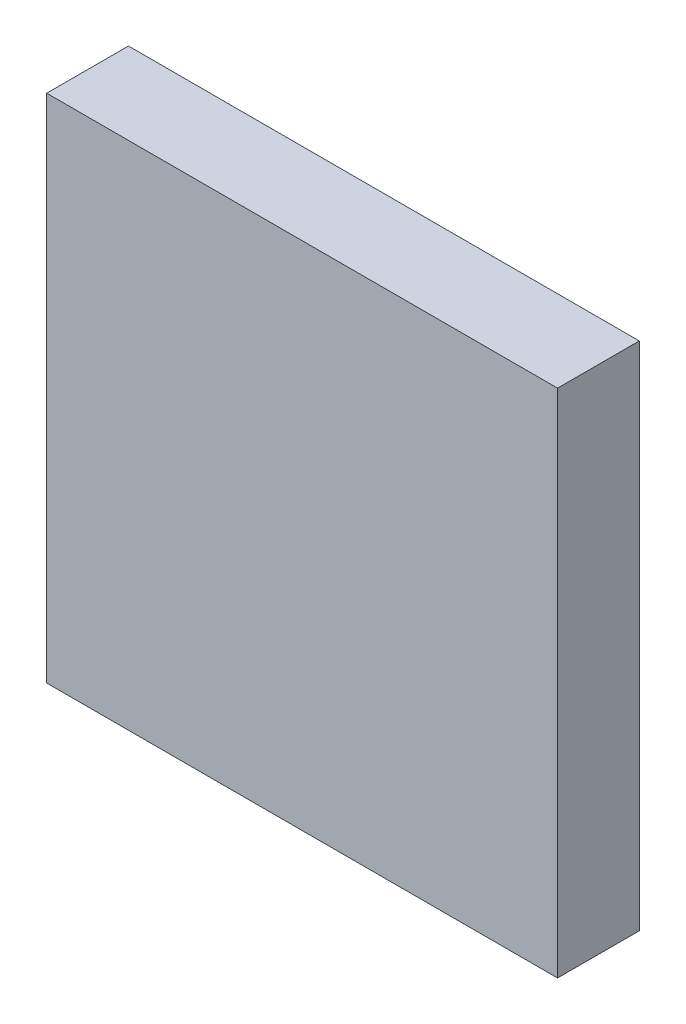
SolidWorks part; units mm, degrees
material "5086-H32, Стержень (SS)"
ref_plane "Спереди" through (0, 0, 0) normal (0, 0, 1) x (1, 0, 0)
ref_plane "Сверху" through (0, 0, 0) normal (0, 1, 0) x (1, 0, 0)
ref_plane "Справа" through (0, 0, 0) normal (1, 0, 0) x (0, 0, -1)
sketch "Эскиз1" plane through (0, 0, 0) normal (0, 0, 1) x (1, 0, 0)
  line L1 (0, 0) -> (50, 0)
  line L2 (0, 0) -> (0, 50)
  line L3 (0, 50) -> (50, 50)
  line L4 (50, 0) -> (50, 50)
  dimension "D1" = 50
  dimension "D2" = 50
extrude "Бобышка-Вытянуть1" add sketch "Эскиз1" along normal blind 8
sketch "Эскиз2" plane through (0, 0, 8) normal (0, 0, 1) x (1, 0, 0)
  line L0 (0, 0) -> (50, 0) construction
  line L1 (0, 50) -> (0, 0) construction
  circle A0 centre (25, 10) radius 4
  dimension "D1" = 8
  dimension "D2" = 10
  dimension "D3" = 25
sketch "Эскиз3" plane through (0, 0, 0) normal (0, -1, 0) x (1, 0, 0)
  line L0 (0, 8) -> (0, 0) construction
  line L1 (0, 0) -> (50, 0) construction
  circle A0 centre (25, 4) radius 2.5
  dimension "D1" = 5
  dimension "D2" = 25
  dimension "D3" = 4
hole_wizard "Отверстие обработанное метчиком M63" positions "Эскиз8" profile "Эскиз9" tap size "M6" standard "ISO"
sketch "Эскиз8" plane through (0, 0, 0) normal (0, -1, 0) x (-1, 0, 0)
  point P0 (-25, -4)
sketch "Эскиз9" plane through (25, 0, 4) normal (1, 0, 0) x (0, 0, -1)
  line L0 (0, 0) -> (0, 15.5022)
  line L1 (0, 15.5022) -> (2.5, 14)
  line L2 (2.5, 14) -> (2.5, 0)
  line L5 (2.5, 0) -> (0, 0)
  line L10 (0, 15.5022) -> (-2.5, 14) construction
  line L11 (0, -6.35) -> (0, 107.95) construction
  dimension "Диаметр сверла" = 5
  dimension "Глубина сверла" = 14
  dimension "Угол заточки сверла" = 118
cosmetic thread "Отверстие резьбы3" parameters "D1"=11, "D2"=6
